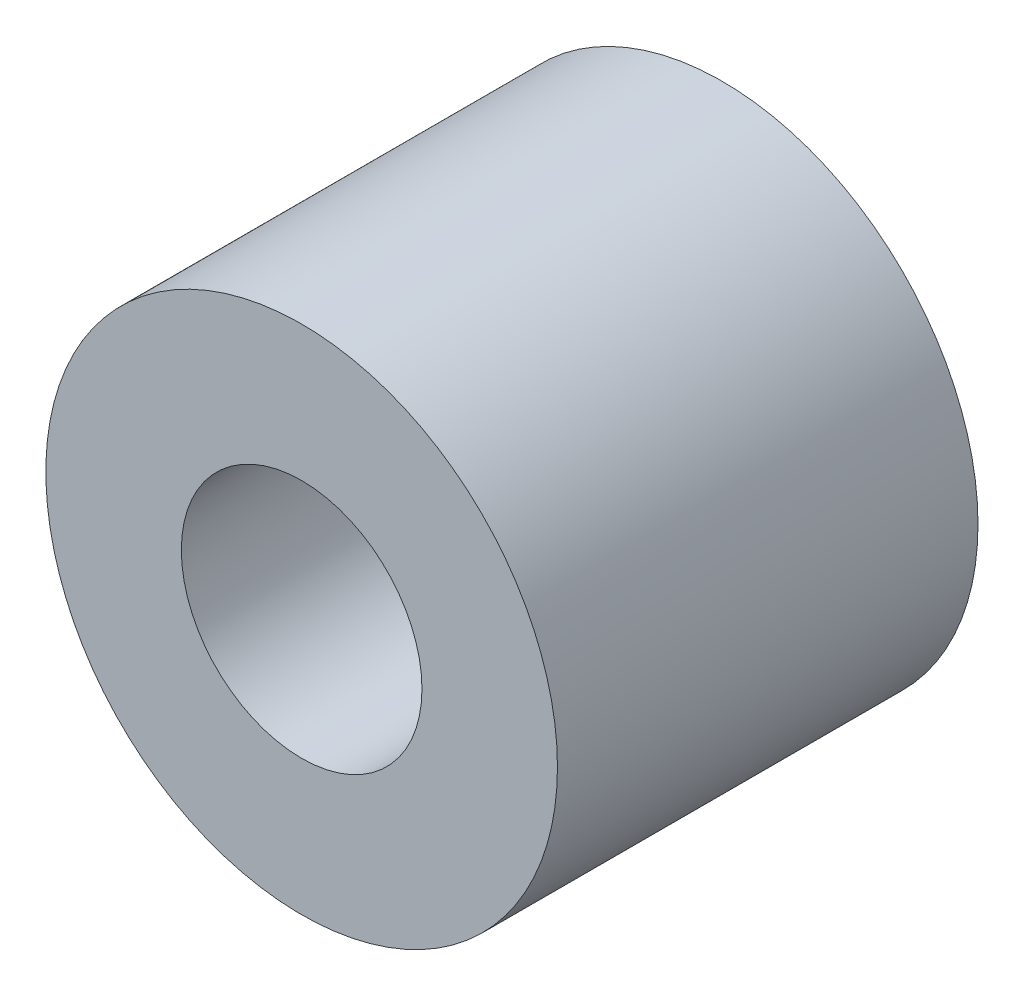
SolidWorks part; units mm, degrees
ref_plane "Front Plane" through (0, 0, 0) normal (0, 0, 1) x (1, 0, 0)
ref_plane "Top Plane" through (0, 0, 0) normal (0, 1, 0) x (1, 0, 0)
ref_plane "Right Plane" through (0, 0, 0) normal (1, 0, 0) x (0, 0, -1)
sketch "Sketch1" plane through (0, 0, 0) normal (0, 0, 1) x (1, 0, 0)
  circle A0 centre (0, 0) radius 10.95
  circle A1 centre (0, 0) radius 5.15
  dimension "D1" = 21.9
  dimension "D2" = 10.3
extrude "Boss-Extrude1" add sketch "Sketch1" along normal blind 18
